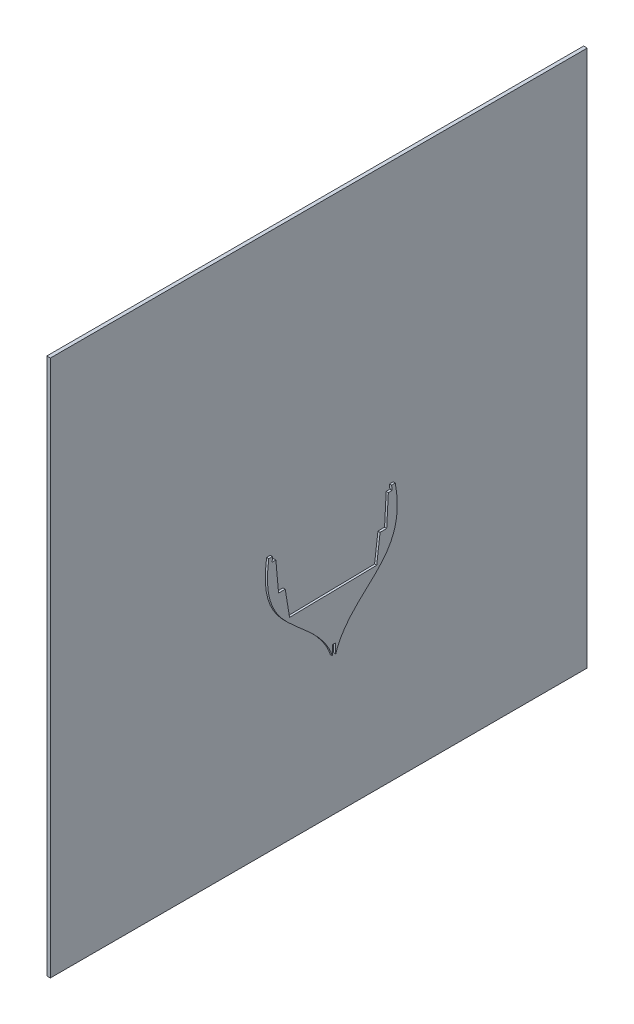
SolidWorks part; units mm, degrees
ref_plane "Plan de face" through (0, 0, 0) normal (0, 0, 1) x (1, 0, 0)
ref_plane "Plan de dessus" through (0, 0, 0) normal (0, 1, 0) x (1, 0, 0)
ref_plane "Plan de droite" through (0, 0, 0) normal (1, 0, 0) x (0, 0, -1)
sketch "Esquisse1" plane through (0, 0, 0) normal (0, 0, 1) x (1, 0, 0)
  point P0 (-20, 0)
  dimension "D1" = 20
sketch3d "Esquisse3D1"
  line L1 (-20, 1121.2893, 777.275) -> (-20, 1121.2893, -722.725)
  line L2 (-20, 1121.2893, 777.275) -> (-20, -378.7107, 777.275)
  line L3 (-20, -378.7107, 777.275) -> (-20, -378.7107, -722.725)
  line L4 (-20, 1121.2893, -722.725) -> (-20, -378.7107, -722.725)
  dimension "D1" = 1500
  dimension "D2" = 1500
extrude "Boss.-Extru.2" add sketch "Esquisse3D1" along direction (1, 0, 0) on the side of the normal blind 10 contours L2 L1 L4 L3
sketch "Esquisse4" plane through (-10, 0, 0) normal (1, 0, 0) x (0, 0, -1)
  line L0 (0, 0) -> (-7.701, 425.1082) construction
  line L1 (169.3944, 339.9131) -> (-188.5193, 333.4294) construction
  line L2 (-187.2006, 249.23) -> (169.0622, 255.6839) construction
  line L3 (-144.268, 175.2448) -> (126.4811, 180.1495) construction
sketch "Esquisse5" plane through (0, 0, 0) normal (1, 0, 0) x (0, 0, -1)
  line L0 (-7.701, 425.1082) -> (0, 0) construction
  line L2 (0, 0) -> (-0.4499, 24.8349) construction
  line L3 (-0.4499, 24.8349) -> (33.0202, 171.0574) construction
  line L4 (33.0202, 171.0574) -> (211.8982, 130.2455) construction
  line L5 (211.8982, 130.2455) -> (170.3838, 353.0767) construction
  line L8 (170.3838, 353.0767) -> (160.3838, 352.8955)
  line L9 (160.3838, 352.8955) -> (161.1934, 339.7646)
  line L10 (169.3944, 339.9131) -> (-188.5193, 333.4294) construction
  line L11 (161.1934, 339.7646) -> (151.0185, 339.5802)
  line L12 (151.0185, 339.5802) -> (146.473, 255.2747)
  line L13 (-187.2006, 249.23) -> (169.0622, 255.6839) construction
  line L14 (146.473, 255.2747) -> (127.9947, 254.9399)
  line L15 (127.9947, 254.9399) -> (118.5267, 180.0054)
  line L16 (-144.268, 175.2448) -> (126.4811, 180.1495) construction
  line L17 (118.5267, 180.0054) -> (-124.9685, 175.5944)
  line L18 (0, 0) -> (-0.4499, 24.8349) construction
  line L19 (-0.4499, 24.8349) -> (-39.1941, 169.7492) construction
  line L20 (-39.1941, 169.7492) -> (-216.4765, 122.4853) construction
  line L21 (-216.4765, 122.4853) -> (-183.06, 346.6739) construction
  line L22 (-137.1444, 250.1368) -> (-124.9685, 175.5944)
  line L23 (-155.6226, 249.8021) -> (-137.1444, 250.1368)
  line L24 (-163.2186, 333.8877) -> (-155.6226, 249.8021)
  line L25 (-173.3935, 333.7034) -> (-163.2186, 333.8877)
  line L26 (-173.06, 346.8551) -> (-173.3935, 333.7034)
  line L27 (-183.06, 346.6739) -> (-173.06, 346.8551)
  spline S0 degree 4 poles (0, 0) (-0.4499, 24.8349) (33.0202, 171.0574) (211.8982, 130.2455) (170.3838, 353.0767) knots 0 0 0 0 0 1 1 1 1 1
  spline S1 degree 4 poles (0, 0) (-0.4499, 24.8349) (-39.1941, 169.7492) (-216.4765, 122.4853) (-183.06, 346.6739) knots 0 0 0 0 0 1 1 1 1 1
  point P30 (-3.2209, 177.7999)
  dimension "D1" = 10
extrude "Boss.-Extru.3" add sketch "Esquisse5" along normal blind 6 separate body
sketch "Esquisse6" plane through (6, 0, 0) normal (1, 0, 0) x (0, 0, -1)
  line L0 (-4.9126, 22.6946) -> (-5.4017, 49.6946)
  line L1 (-5.4017, 49.6946) -> (3.5983, 49.8577)
  line L2 (3.5983, 49.8577) -> (4.0874, 22.8577)
  line L3 (4.0874, 22.8577) -> (117.0633, -47.527)
  line L4 (117.0633, -47.527) -> (-85.2277, -65.22)
  line L5 (-85.2277, -65.22) -> (-4.9126, 22.6946)
  line L6 (-4.9126, 22.6946) -> (4.0874, 22.8577) construction
  line L7 (-144.268, 175.2448) -> (126.4811, 180.1495) construction
  spline S0 degree 4 poles (-183.06, 346.6739) (-216.4765, 122.4853) (-39.1941, 169.7492) (-0.4499, 24.8349) (0, 0) knots 0 0 0 0 0 1 1 1 1 1 construction
  spline S1 degree 4 poles (0, 0) (-0.4499, 24.8349) (33.0202, 171.0574) (211.8982, 130.2455) (170.3838, 353.0767) knots 0 0 0 0 0 1 1 1 1 1 construction
  dimension "D1" = 9
  dimension "D2" = 27
extrude "Enlèv. mat.-Extru.1" cut sketch "Esquisse6" against normal blind 6
